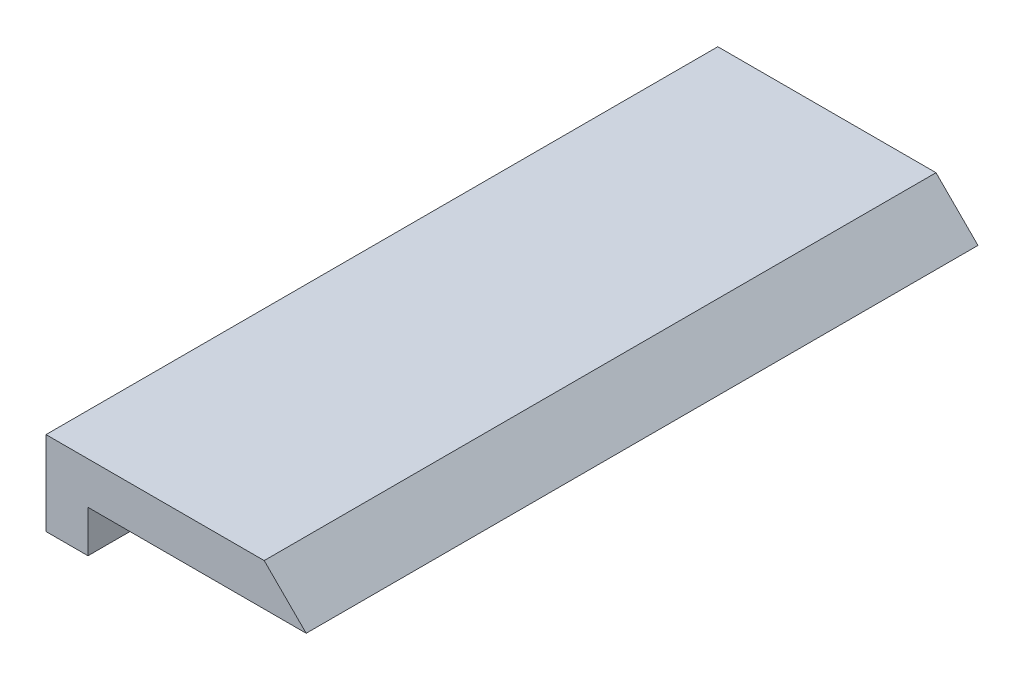
SolidWorks part; units mm, degrees
ref_plane "Front Plane" through (0, 0, 0) normal (0, 0, 1) x (1, 0, 0)
ref_plane "Top Plane" through (0, 0, 0) normal (0, 1, 0) x (1, 0, 0)
ref_plane "Right Plane" through (0, 0, 0) normal (1, 0, 0) x (0, 0, -1)
sketch "Sketch1" plane through (0, 0, 0) normal (0, 0, 1) x (1, 0, 0)
  line L0 (0, 0) -> (0, -6.35)
  line L1 (0, -6.35) -> (-6.35, -6.35)
  line L2 (-6.35, -6.35) -> (-6.35, 6.35)
  line L5 (33, 0) -> (0, 0)
  line L6 (33, 0) -> (26.65, 6.35)
  line L7 (26.65, 6.35) -> (-6.35, 6.35)
  dimension "D1" = 45
  dimension "D2" = 6.35
  dimension "D3" = 6.35
  dimension "D4" = 6.35
  dimension "D5" = 33
extrude "Boss-Extrude1" add sketch "Sketch1" along normal mid plane 101.6
